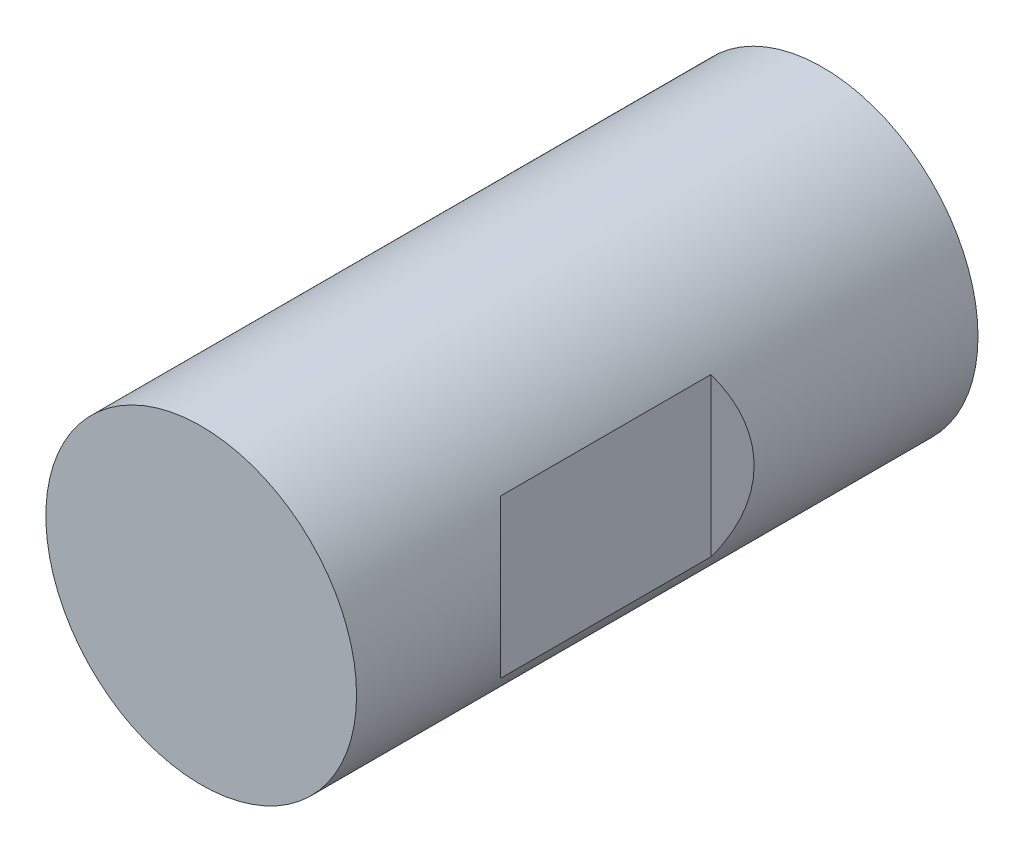
SolidWorks part; units mm, degrees
ref_plane "Front Plane" through (0, 0, 0) normal (0, 0, 1) x (1, 0, 0)
ref_plane "Top Plane" through (0, 0, 0) normal (0, 1, 0) x (1, 0, 0)
ref_plane "Right Plane" through (0, 0, 0) normal (1, 0, 0) x (0, 0, -1)
sketch "Sketch1" plane through (0, 0, 0) normal (0, 0, 1) x (1, 0, 0)
  circle A0 centre (0, 0) radius 15.5
  dimension "D1" = 31
extrude "Boss-Extrude1" add sketch "Sketch1" along normal blind 62
sketch "Sketch2" plane through (0, 0, 0) normal (0, 1, 0) x (1, 0, 0)
  line L0 (-15.5, -22.3371) -> (-13.35, -24.5)
  line L1 (-15.5, 0) -> (-15.5, -62) construction
  line L2 (-13.35, -24.5) -> (-13.35, -45.5)
  line L3 (-13.35, -35) -> (-27.5713, -35) construction
  line L5 (-15.5, -47.6629) -> (-13.35, -45.5)
  line L6 (0, 0) -> (0, -15.5504) construction
  line L7 (15.5, -47.6629) -> (13.35, -45.5)
  line L8 (15.5, -22.3371) -> (15.5, -47.6629)
  line L9 (13.35, -24.5) -> (13.35, -45.5)
  line L10 (15.5, -22.3371) -> (13.35, -24.5)
  line L11 (-15.5, -62) -> (15.5, -62) construction
  line L12 (-15.5, -22.3371) -> (-15.5, -47.6629)
  point P9 (-15.349, -35)
  dimension "D1" = 16.5
  dimension "D2" = 26.7
  dimension "D3" = 21
extrude "Cut-Extrude1" cut sketch "Sketch2" against normal through all both and the other way through all contours L12 L5 L2 L0 | L7 L9 L10 L8
